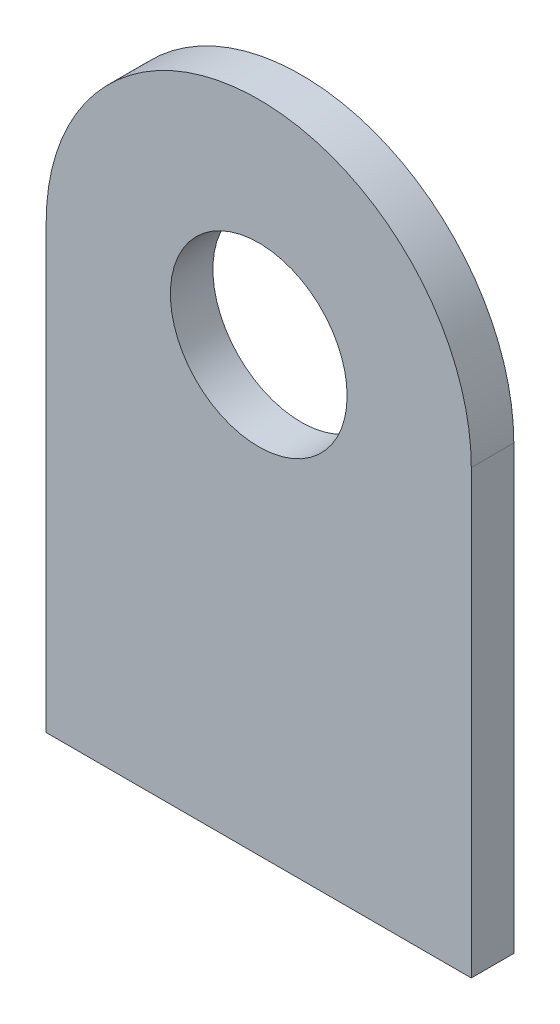
SolidWorks part; units mm, degrees
material "ASTM A36 Steel"
ref_plane "X-Y Datum" through (0, 0, 0) normal (0, 0, 1) x (1, 0, 0)
ref_plane "X-Z Datum" through (0, 0, 0) normal (0, 1, 0) x (1, 0, 0)
ref_plane "Y-Z Datum" through (0, 0, 0) normal (1, 0, 0) x (0, 0, -1)
sketch "Sketch1" plane through (0, 0, 0) normal (0, 0, 1) x (1, 0, 0)
  line L0 (-7.9375, 0) -> (-7.9375, -16.51)
  line L1 (-7.9375, -16.51) -> (7.9375, -16.51)
  line L2 (7.9375, -16.51) -> (7.9375, 0)
  circle A0 centre (0, 0) radius 7.9375
  circle A1 centre (0, 0) radius 3
  dimension "D1" = 6
  dimension "D2" = 15.875
  dimension "D3" = 16.51
extrude "Boss-Extrude1" add sketch "Sketch1" along normal blind 1.5875 contours A0 A1 | A0 L0 L1 L2 | A1
hole_wizard "M6 Clearance Hole1" positions "Sketch2" profile "Sketch3" hole size "M6" standard "ANSI Metric" end condition through all
sketch "Sketch2" plane through (0, 0, 1.5875) normal (0, 0, 1) x (1, 0, 0)
  point P0 (0, 0)
sketch "Sketch3" plane through (0, 0, 1.5875) normal (1, 0, 0) x (0, -1, 0)
  line L0 (0, 0) -> (0, 1.5875)
  line L1 (0, 1.5875) -> (3.3, 1.5875)
  line L2 (3.3, 1.5875) -> (3.3, 0)
  line L5 (3.3, 0) -> (0, 0)
  line L11 (0, -6.35) -> (0, 107.95) construction
  dimension "Thru Hole Dia." = 6.6
  dimension "Thru Hole Depth" = 1.5875
sketch "Sketch4" [suppressed] plane through (0, 0, 2.54) normal (0, 0, 1) x (1, 0, 0)
  line L1 (57.1174, 89.0913) -> (2.6108, -25.4)
  line L3 (1.0953, -29.3967) -> (-107.8628, 152.3221)
  line M3 (-7.9375, 0) -> (-7.9375, -25.4)
  line M4 (-7.9375, -25.4) -> (7.9375, -25.4)
  line M5 (7.9375, -25.4) -> (7.9375, 0)
extrude "Cut-Extrude1" [suppressed] cut sketch "Sketch4" against normal through all contours L3 M4 M3 | L1 M5 M4
